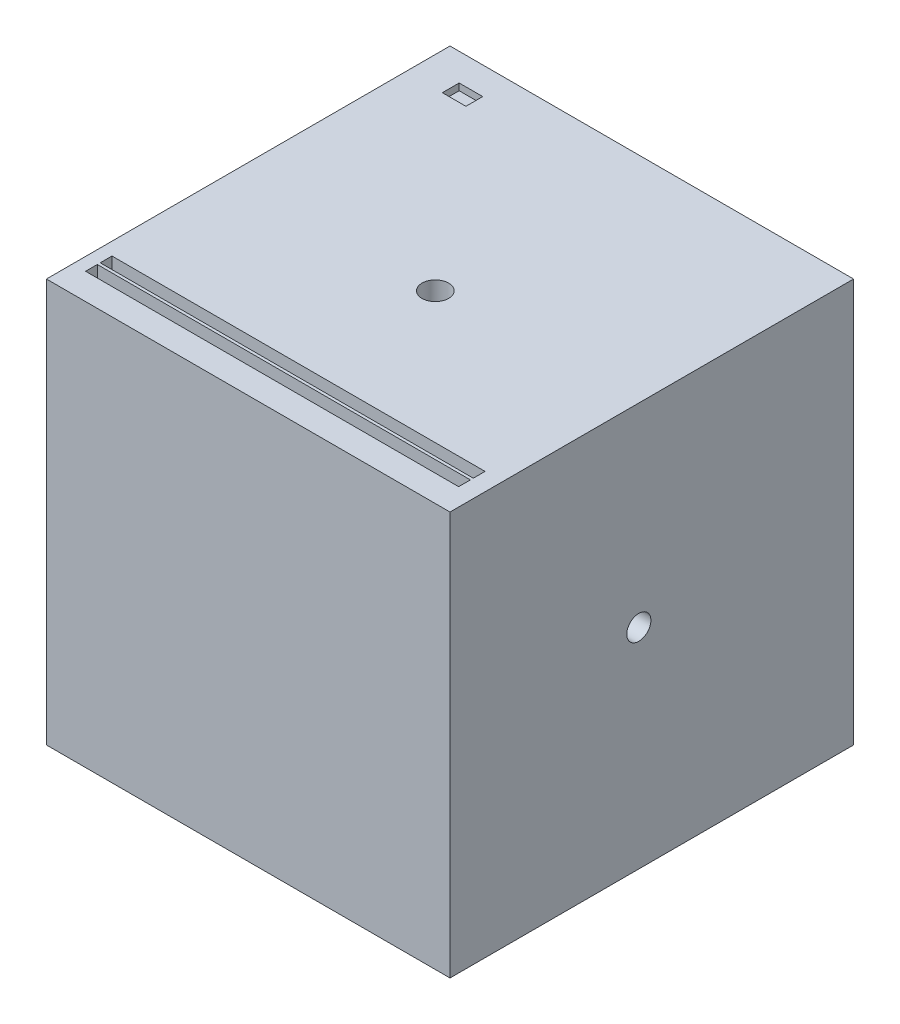
SolidWorks part; units mm, degrees
ref_plane "Plano frontal" through (0, 0, 0) normal (0, 0, 1) x (1, 0, 0)
ref_plane "Plano superior" through (0, 0, 0) normal (0, 1, 0) x (1, 0, 0)
ref_plane "Plano direito" through (0, 0, 0) normal (1, 0, 0) x (0, 0, -1)
sketch "Esboço1" plane through (0, 0, 0) normal (0, 0, 1) x (1, 0, 0)
  line L1 (-72.7029, 54.5893) -> (47.2971, 54.5893)
  line L2 (-72.7029, 54.5893) -> (-72.7029, -65.4107)
  line L3 (-72.7029, -65.4107) -> (47.2971, -65.4107)
  line L4 (47.2971, 54.5893) -> (47.2971, -65.4107)
  line L5 (-72.7029, 54.5893) -> (47.2971, -65.4107) construction
  line L6 (-72.7029, -65.4107) -> (47.2971, 54.5893) construction
  point P4 (-12.7029, -5.4107)
  dimension "D1" = 120
  dimension "D2" = 120
extrude "Ressalto-extrusão1" add sketch "Esboço1" along normal blind 120
sketch "Esboço2" plane through (-72.7029, 0, 0) normal (-1, 0, 0) x (0, 0, 1)
  line L1 (88.6539, 37.7941) -> (33.6539, 37.7941)
  line L2 (88.6539, 37.7941) -> (88.6539, -50.2059)
  line L3 (88.6539, -50.2059) -> (33.6539, -50.2059)
  line L4 (33.6539, 37.7941) -> (33.6539, -50.2059)
  line L5 (88.6539, 37.7941) -> (33.6539, -50.2059) construction
  line L6 (88.6539, -50.2059) -> (33.6539, 37.7941) construction
  point P4 (61.1539, -6.2059)
  dimension "D1" = 88
  dimension "D2" = 55
  dimension "D6" = 55
extrude "Corte-extrusão2" cut sketch "Esboço2" against normal blind 5
sketch "Esboço3" plane through (0, 54.5893, 0) normal (0, 1, 0) x (1, 0, 0)
  line L1 (42.0588, -112.1916) -> (-68.8776, -112.1916)
  line L2 (42.0588, -112.1916) -> (42.0588, -108.6916)
  line L3 (42.0588, -108.6916) -> (-68.8776, -108.6916)
  line L4 (-68.8776, -112.1916) -> (-68.8776, -108.6916)
  line L5 (42.0588, -112.1916) -> (-68.8776, -108.6916) construction
  line L6 (42.0588, -108.6916) -> (-68.8776, -112.1916) construction
  line L7 (42.0588, -104.334) -> (-68.8776, -104.334)
  line L8 (42.0588, -104.334) -> (42.0588, -107.834)
  line L9 (42.0588, -107.834) -> (-68.8776, -107.834)
  line L10 (-68.8776, -104.334) -> (-68.8776, -107.834)
  line L11 (42.0588, -104.334) -> (-68.8776, -107.834) construction
  line L12 (42.0588, -107.834) -> (-68.8776, -104.334) construction
  point P4 (-13.4094, -110.4416)
  point P9 (-13.4094, -106.084)
  dimension "D1" = 3.5
  dimension "D2" = 110.9364
  dimension "D3" = 3.5
  dimension "D4" = 110.9364
extrude "Corte-extrusão3" cut sketch "Esboço3" against normal blind 142
sketch "Esboço4" plane through (0, 54.5893, 0) normal (0, 1, 0) x (1, 0, 0)
  line L1 (-54.8153, -13.1609) -> (-61.8153, -13.1609)
  line L2 (-54.8153, -13.1609) -> (-54.8153, -8.1609)
  line L3 (-54.8153, -8.1609) -> (-61.8153, -8.1609)
  line L4 (-61.8153, -13.1609) -> (-61.8153, -8.1609)
  line L5 (-54.8153, -13.1609) -> (-61.8153, -8.1609) construction
  line L6 (-54.8153, -8.1609) -> (-61.8153, -13.1609) construction
  point P4 (-58.3153, -10.6609)
  dimension "D1" = 5
  dimension "D2" = 7
extrude "Corte-extrusão5" cut sketch "Esboço4" against normal blind 2
sketch "Esboço5" plane through (-72.7029, 0, 0) normal (-1, 0, 0) x (0, 0, 1)
  line L1 (15.3926, -43.9999) -> (10.3926, -43.9999)
  line L2 (15.3926, -43.9999) -> (15.3926, -55.9999)
  line L3 (15.3926, -55.9999) -> (10.3926, -55.9999)
  line L4 (10.3926, -43.9999) -> (10.3926, -55.9999)
  line L5 (15.3926, -43.9999) -> (10.3926, -55.9999) construction
  line L6 (15.3926, -55.9999) -> (10.3926, -43.9999) construction
  point P4 (12.8926, -49.9999)
  dimension "D1" = 12
  dimension "D2" = 5
extrude "Corte-extrusão6" cut sketch "Esboço5" against normal blind 10
sketch "Esboço6" plane through (0, 54.5893, 0) normal (0, 1, 0) x (1, 0, 0)
  circle A0 centre (-11.856, -65.2109) radius 3.9616
extrude "Corte-extrusão7" cut sketch "Esboço6" against normal blind 230
sketch "Esboço7" plane through (47.2971, 0, 0) normal (1, 0, 0) x (0, 0, -1)
  circle A0 centre (-63.8495, -3.1808) radius 3.5922
extrude "Corte-extrusão8" cut sketch "Esboço7" against normal blind 90
